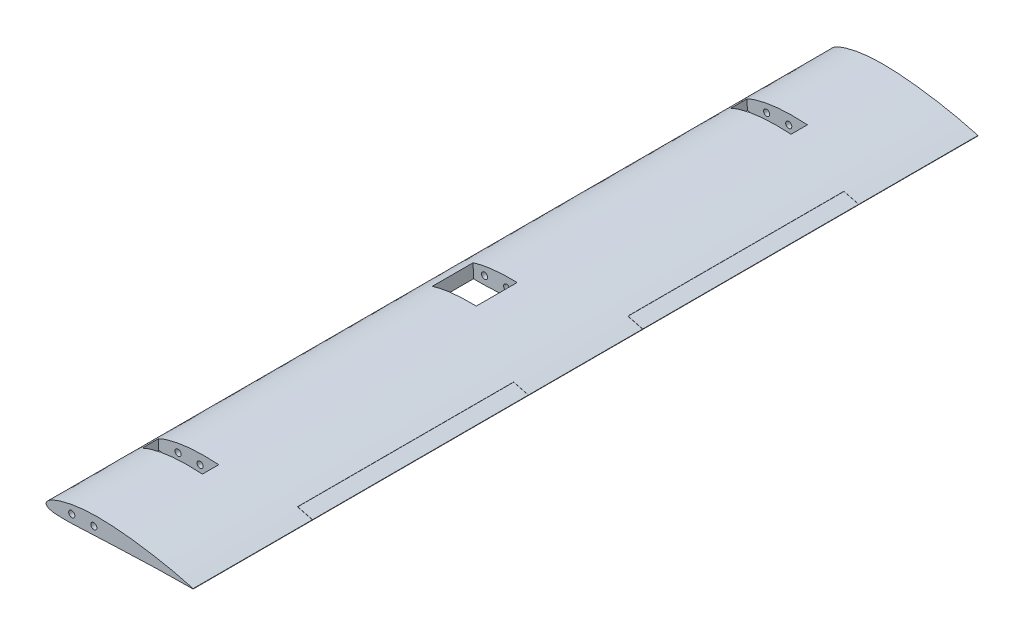
SolidWorks part; units mm, degrees
material "AFL blue foam"
ref_plane "Front Plane" through (0, 0, 0) normal (0, 0, 1) x (1, 0, 0)
ref_plane "Top Plane" through (0, 0, 0) normal (0, 1, 0) x (1, 0, 0)
ref_plane "Right Plane" through (0, 0, 0) normal (1, 0, 0) x (0, 0, -1)
other "Center of Mass"
curve "NACA 4412"
  spline degree 3 poles (25.4, 0.033, 0) (24.9771, 0.1481, 0) (24.1334, 0.3778, 0) (22.4431, 0.7955, 0) (20.3293, 1.2569, 0) (17.7869, 1.7118, 0) (15.2464, 2.0846, 0) (12.7045, 2.3505, 0) (10.1628, 2.5164, 0) (8.041, 2.5181, 0) (6.3469, 2.4009, 0) (5.0745, 2.2465, 0) (3.7995, 2.0188, 0) (2.7428, 1.745, 0) (1.8961, 1.4685, 0) (1.2577, 1.2074, 0) (0.7129, 0.9251, 0) (0.2401, 0.5874, 0) (-0.1715, 0.0442, 0) (0.2727, -0.3711, 0) (0.7261, -0.5342, 0) (1.266, -0.6443, 0) (1.9036, -0.7002, 0) (2.7513, -0.7398, 0) (3.8103, -0.7368, 0) (5.0806, -0.7013, 0) (6.3499, -0.6336, 0) (8.0433, -0.5544, 0) (10.1596, -0.4528, 0) (12.7001, -0.3574, 0) (15.2397, -0.2514, 0) (17.7796, -0.1611, 0) (20.3198, -0.0947, 0) (22.4366, -0.061, 0) (24.13, -0.0388, 0) (24.9767, -0.035, 0) (25.4, -0.033, 0) knots 0 0 0 0 0.025305 0.050488 0.10052 0.150191 0.199587 0.24874 0.297716 0.346601 0.371103 0.395726 0.42057 0.445825 0.458702 0.47192 0.485786 0.493461 0.506863 0.516148 0.522766 0.535269 0.547551 0.559786 0.584229 0.608681 0.633151 0.657622 0.706558 0.755482 0.804406 0.85332 0.902221 0.951113 0.975557 1 1 1 1
sketch "Sketch2" plane through (0, 0, 0) normal (0, 0, 1) x (1, 0, 0)
  line L1 (228.6, 12.387) -> (228.6, 11.7928)
  line L2 (40.005, 31.2493) -> (40.005, 5.6305) construction
  line L3 (68.58, 34.393) -> (68.58, 6.961) construction
  line L4 (74.2832, 19.3375) -> (40.005, 18.4399) construction
  line L5 (0, 0) -> (0, 12.7) construction
  line L6 (40.005, 18.4399) -> (60.8151, 18.4399) construction
  line L7 (68.58, 34.393) -> (228.6056, 20.677) construction
  line L8 (228.6056, 20.677) -> (68.58, 6.961) construction
  line L9 (68.58, 20.677) -> (228.6056, 20.677) construction
  line L11 (59.9523, -93.7228) -> (219.9779, -107.4388)
  line L12 (219.9779, -107.4388) -> (59.9523, -121.1548)
  line L14 (61.264, -169.3292) -> (106.984, -169.3292)
  line L16 (106.984, -141.8972) -> (61.264, -141.8972)
  line L17 (106.984, -141.8972) -> (221.2897, -155.6132)
  line L18 (106.984, -169.3292) -> (221.2897, -155.6132)
  circle A0 centre (40.005, 18.4399) radius 4.7625
  circle A1 centre (74.2832, 19.3375) radius 4.7625
  circle A2 centre (30.4326, -102.8904) radius 4.7625
  circle A3 centre (47.3544, -108.3106) radius 4.7625
  circle A4 centre (31.7443, -151.0648) radius 4.7625
  circle A5 centre (48.6661, -156.485) radius 4.7625
  ellipse E0 centre (68.58, 20.677) end of major axis (0, 20.677) minor radius 13.716 (68.58, 34.393) -> (68.58, 6.961) ccw construction
  ellipse E1 centre (59.9523, -107.4388) end of major axis (128.5323, -107.4388) minor radius 13.716 (59.9523, -93.7228) -> (59.9523, -121.1548) ccw
  ellipse E2 centre (61.264, -155.6132) end of major axis (129.844, -155.6132) minor radius 13.716 (61.264, -141.8972) -> (61.264, -169.3292) ccw
  spline S1 degree 3 poles (228.6, 12.387) (224.795, 13.4228) (217.2034, 15.4895) (201.9951, 19.2471) (182.9766, 23.3988) (160.101, 27.4914) (137.2432, 30.846) (114.3726, 33.2389) (91.504, 34.7313) (72.413, 34.7464) (57.1699, 33.6918) (45.7222, 32.3028) (34.2497, 30.2543) (24.7428, 27.7908) (17.1245, 25.3027) (11.3801, 22.9538) (6.4787, 20.4136) (2.2242, 17.375) (-1.4793, 12.488) (2.5182, 8.7506) (6.5972, 7.2835) (11.455, 6.2932) (17.1921, 5.7898) (24.819, 5.4335) (34.3469, 5.4602) (45.7763, 5.78) (57.1976, 6.389) (72.4334, 7.1015) (91.4748, 8.016) (114.3327, 8.8746) (137.1833, 9.8281) (160.036, 10.6401) (182.8906, 11.2375) (201.9369, 11.5408) (217.1729, 11.7405) (224.791, 11.7754) (228.6, 11.7928) knots 0 0 0 0 0.025305 0.050488 0.10052 0.150191 0.199587 0.24874 0.297716 0.346601 0.371103 0.395726 0.42057 0.445825 0.458702 0.47192 0.485786 0.493461 0.506863 0.516148 0.522766 0.535269 0.547551 0.559786 0.584229 0.608681 0.633151 0.657622 0.706558 0.755482 0.804406 0.85332 0.902221 0.951113 0.975557 1 1 1 1
  point P11 (40.005, 18.4399)
  dimension "D3" = 9.525
  dimension "D4" = 9.525
  dimension "D10" = 9.525
  dimension "D11" = 9.525
  dimension "D12" = 9.525
  dimension "D13" = 9.525
  dimension "D1" = 228.6
  dimension "D5" = 34.29
  dimension "D6" = 12.7
  dimension "D8" = 1.5
  dimension "D9" = 40.005
  dimension "D2" = 68.58
  dimension "D7" = 27.432
  dimension "D14" = 45.72
extrude "Extrude airfoil" add sketch "Sketch2" along normal blind 1219.2
sketch "Sketch3" plane through (0, 0, 0) normal (0, 1, 0) x (1, 0, 0)
  line L1 (228.6, -520.7) -> (205.74, -520.7)
  line L4 (205.74, -520.7) -> (205.74, -185.42)
  line L5 (228.6, -185.42) -> (205.74, -185.42)
  line L8 (0, 0) -> (0, -1219.2) construction
  line L9 (0, -609.6) -> (228.6, -609.6) construction
  line L10 (228.6, -1033.78) -> (228.6, -698.5)
  line L15 (228.6, -185.42) -> (228.6, -520.7)
  line L17 (228.6, -1219.2) -> (228.6, 0) construction
  line L18 (228.6, -1033.78) -> (205.74, -1033.78)
  line L19 (205.74, -698.5) -> (205.74, -1033.78)
  line L20 (228.6, -698.5) -> (205.74, -698.5)
  dimension "D1" = 22.86
  dimension "D2" = 335.28
  dimension "D3" = 88.9
extrude "Ailerons" cut sketch "Sketch3" against normal through all and the other way through all thin
ref_plane "Plane1" through (-0.4551, 17.3804, 0) normal (-0.0262, 0.9997, 0) x (0, 0, -1)
sketch "Sketch5" plane through (-0.4551, 17.3804, 0) normal (-0.0262, 0.9997, 0) x (0, 0, -1)
  line L0 (0, 0) -> (-1219.2, 0)
  line L1 (-609.6, 0) -> (-609.6, -227.3868) construction
  line L2 (-609.6, -57.15) -> (-1066.8, -57.15) construction
  line L3 (-139.7, -10.16) -> (-165.1, -104.14) construction
  line L4 (-1079.5, -104.14) -> (-1054.1, -104.14)
  line L5 (-1079.5, -104.14) -> (-1079.5, -10.16)
  line L6 (-1079.5, -10.16) -> (-1054.1, -10.16)
  line L7 (-1054.1, -104.14) -> (-1054.1, -10.16)
  line L8 (-1079.5, -104.14) -> (-1054.1, -10.16) construction
  line L9 (-1079.5, -10.16) -> (-1054.1, -104.14) construction
  line L10 (-139.7, -104.14) -> (-165.1, -10.16) construction
  line L11 (-165.1, -104.14) -> (-165.1, -10.16)
  line L12 (-139.7, -104.14) -> (-139.7, -10.16)
  line L13 (-139.7, -104.14) -> (-165.1, -104.14)
  line L14 (-139.7, -10.16) -> (-165.1, -10.16)
  line L16 (-577.85, -91.44) -> (-641.35, -91.44)
  line L17 (-577.85, -91.44) -> (-577.85, -22.86)
  line L18 (-577.85, -22.86) -> (-641.35, -22.86)
  line L19 (-641.35, -91.44) -> (-641.35, -22.86)
  point P19 (-609.6, -22.86)
  dimension "D1" = 1219.2
  dimension "D2" = 57.15
  dimension "D3" = 25.4
  dimension "D4" = 93.98
  dimension "D5" = 457.2
  dimension "D6" = 22.86
  dimension "D7" = 91.44
  dimension "D8" = 31.75
extrude "Cut-Extrude1" cut sketch "Sketch5" against normal through all and the other way through all contours L12 L14 L11 L13 | L7 L6 L5 L4 | L18 L19 L16 L17
equation "\"D1@Extrude airfoil\"=\"span\""
equation "\"D1@Sketch2\"= \"wing_chord\""
equation "\"D1@Sketch3\"=\"wing_chord\"*0.1"
equation "\"D2@Sketch3\"=\"span\"/2*0.55"
equation "\"D3@Sketch2\"=\"wing_spar_d\""
equation "\"D4@Sketch2\"=\"wing_spar_d\""
equation "\"D8@Sketch2\"=\"wing_angle\""
equation "\"D1@Sketch5\"=\"span\""
equation "\"D2@Sketch5\"=\"x_cg_from_le\""
equation "\"D3@Sketch5\"=\"boom_mount_l\""
equation "\"D5@Sketch5\"=\"wing_mount_y\"/2"
equation "\"D5@Sketch2\"= \"wing_spar_spacing\""
equation "\"D9@Sketch2\"= \"x_cg_from_le\" - \"wing_spar_spacing\"/2"
equation "\"D6@Sketch5\"= \"x_cg_from_le\" - \"wing_spar_spacing\""
equation "\"D7@Sketch5\"= \"wing_chord\"*0.4"
equation "\"D8@Sketch5\"= \"wing_mount_l\"/2"
equation "\"span\"= 48"
equation "\"wing_chord\"= 9"
equation "\"fuse_len\"= 15"
equation "\"fuse_height\"= 5"
equation "\"fuse_wid\"= 5"
equation "\"foam_t\"= 0.1875"
equation "\"main_spar_len\"= 36"
equation "\"x_fuse_to_wing\"= 3"
equation "\"x_cg_from_le\"= 2.25"
equation "\"boom_len\"= 30"
equation "\"wing_angle\"= 1.5"
equation "\"boom_d\"= 0.75"
equation "\"wing_spar_d\"= 0.375"
equation "\"wing_spar_l\"= 48"
equation "\"wing_spar_spacing\"= 1.35"
equation "\"wing_mount_l\"= 2.5"
equation "\"boom_mount_l\"= 1"
equation "\"vstab_span\"= 6.5"
equation "\"hstab_span\"= 15.25"
equation "\"tail_chord\"= 5"
equation "\"wing_spar_ID\"= 0.25"
equation "\"fuse_inner_arc_length\" = 0.5"
equation "\"fuse_inner_r\" = \"fuse_inner_arc_length\" * 4 / (2*pi)"
equation "\"fuse_outer_r\" = \"fuse_inner_r\" + \"foam_t\""
equation "\"wing_mount_bolt_spacing\" = \"wing_mount_l\" * 0.5"
equation "\"fuse_inner_h\" = \"fuse_height\" - 2 * \"foam_t\""
equation "\"fuse_inner_w\" = \"fuse_wid\" - 2 * \"fuse_outer_r\""
equation "\"wing_mount_y\" = 36"
equation "\"D2@Sketch2\"=\"wing_chord\"*0.3"
equation "\"D7@Sketch2\"=\"wing_chord\"*0.12"
equation "\"D14@Sketch2\"=\"wing_chord\"*0.2"
